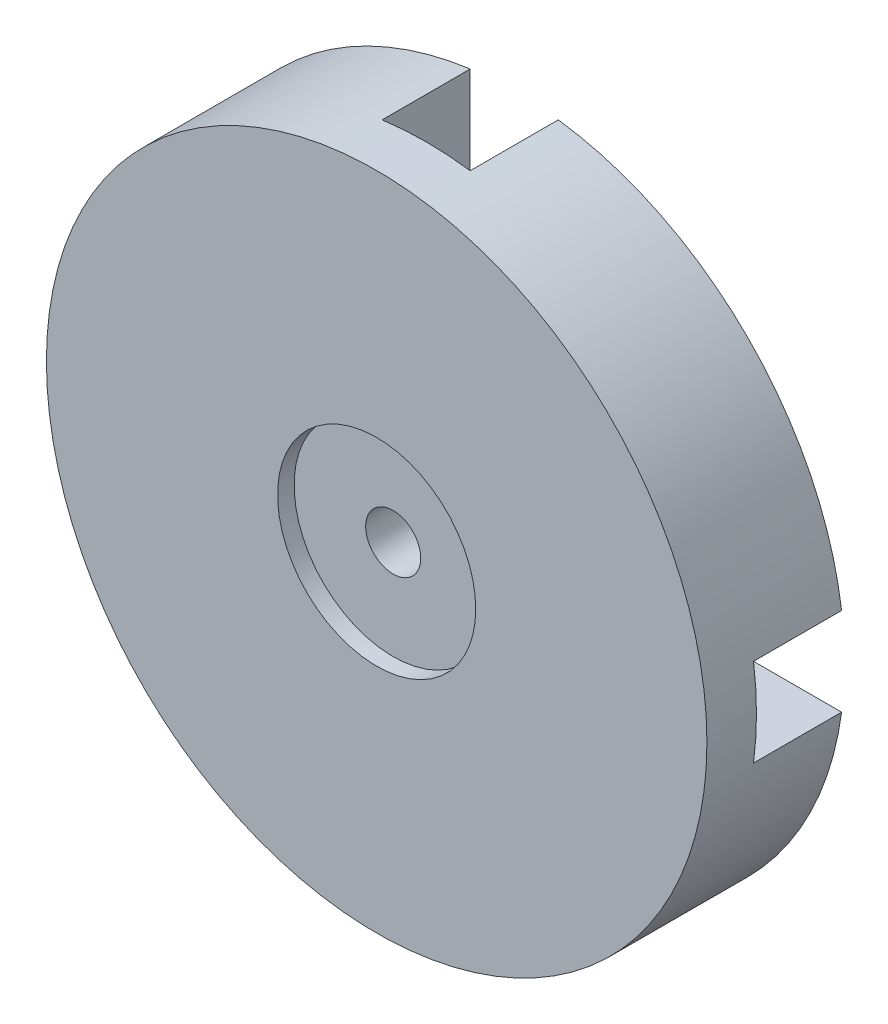
SolidWorks part; units mm, degrees
ref_plane "Plan de face" through (0, 0, 0) normal (0, 0, 1) x (1, 0, 0)
ref_plane "Plan de dessus" through (0, 0, 0) normal (0, 1, 0) x (1, 0, 0)
ref_plane "Plan de droite" through (0, 0, 0) normal (1, 0, 0) x (0, 0, -1)
sketch "Esquisse1" plane through (0, 0, 0) normal (0, 0, 1) x (1, 0, 0)
  circle A0 centre (0, 0) radius 60
  dimension "D1" = 120
extrude "Boss.-Extru.1" add sketch "Esquisse1" along normal blind 25
sketch "Esquisse2" plane through (0, 0, 25) normal (0, 0, 1) x (1, 0, 0)
  circle A0 centre (0, 0) radius 18
  dimension "D1" = 36
extrude "Enlèv. mat.-Extru.1" cut sketch "Esquisse2" against normal blind 3
sketch "Esquisse3" plane through (0, 0, 22) normal (0, 0, 1) x (1, 0, 0)
  circle A0 centre (0, 0) radius 5
  dimension "D1" = 10
extrude "Enlèv. mat.-Extru.2" cut sketch "Esquisse3" against normal through all both and the other way through all
sketch "Esquisse4" plane through (0, 0, 0) normal (0, 0, -1) x (-1, 0, 0)
  line L0 (0, 0) -> (60, 0) construction
  line L1 (0, 0) -> (0, 60) construction
  line L2 (15, 8) -> (60, 8)
  line L3 (60, 8) -> (60, -8)
  line L4 (15, -8) -> (60, -8)
  line L5 (15, -8) -> (15, 8)
  line L6 (8, -15) -> (8, -60)
  line L7 (8, -60) -> (-8, -60)
  line L8 (-8, -15) -> (-8, -60)
  line L9 (-8, -15) -> (8, -15)
  line L10 (-15, -8) -> (-60, -8)
  line L11 (-60, -8) -> (-60, 8)
  line L12 (-15, 8) -> (-60, 8)
  line L13 (-15, 8) -> (-15, -8)
  line L14 (-8, 15) -> (-8, 60)
  line L15 (-8, 60) -> (8, 60)
  line L16 (8, 15) -> (8, 60)
  line L17 (8, 15) -> (-8, 15)
  circle A0 centre (0, 0) radius 60 construction
  point P11 (60, 0)
  point P12 (-60, 0)
  point P13 (0, 0)
  point P14 (3.962, 5.3262)
  point P19 (0, -60)
  point P24 (-60, 0)
  point P29 (0, 60)
  point P30 (0, 0)
  dimension "D1" = 16
  dimension "D2" = 45
  dimension "D3" = 4
extrude "Enlèv. mat.-Extru.3" cut sketch "Esquisse4" against normal blind 16
